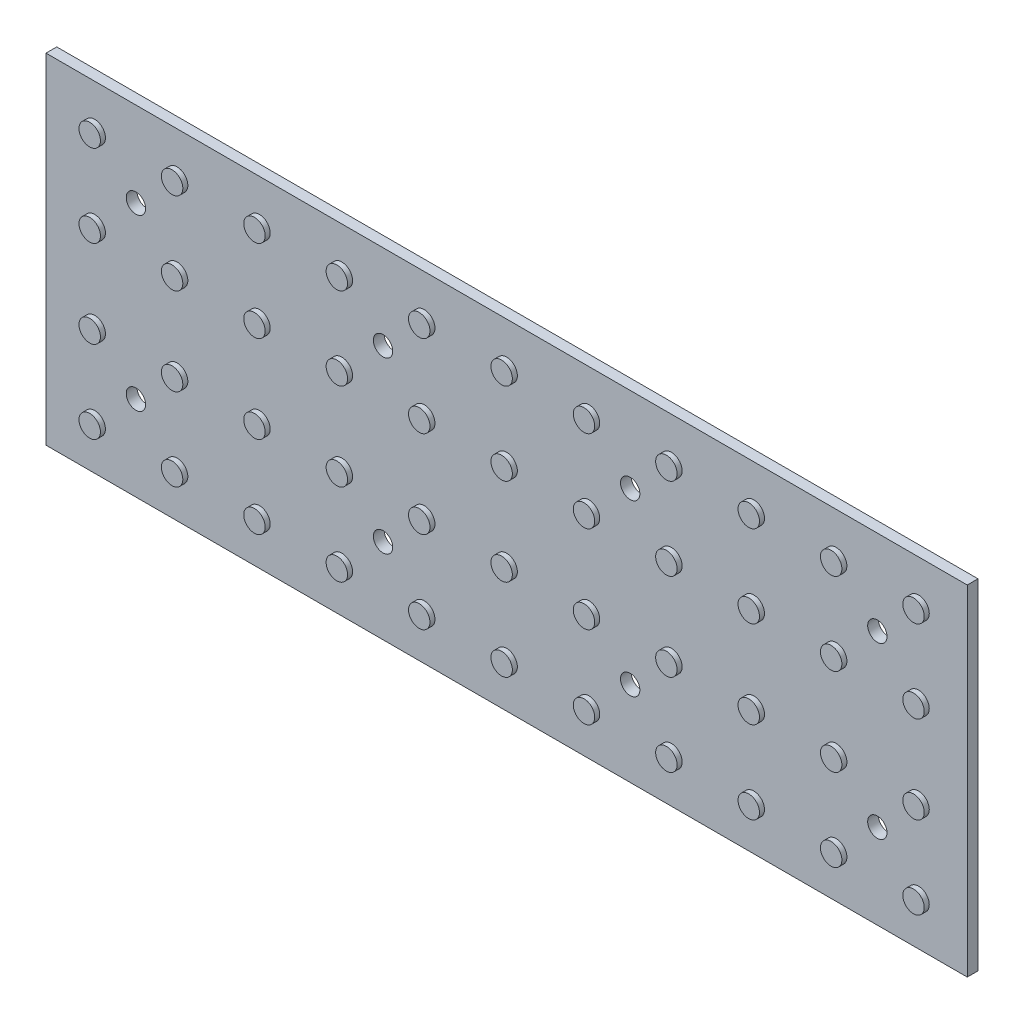
SolidWorks part; units mm, degrees
ref_plane "Front Plane" through (0, 0, 0) normal (0, 0, 1) x (1, 0, 0)
ref_plane "Top Plane" through (0, 0, 0) normal (0, 1, 0) x (1, 0, 0)
ref_plane "Right Plane" through (0, 0, 0) normal (1, 0, 0) x (0, 0, -1)
sketch "Sketch1" plane through (0, 0, 0) normal (0, 0, 1) x (1, 0, 0)
  line L1 (257.2, 0) -> (0, 0)
  line L2 (257.2, 0) -> (257.2, 94.8)
  line L3 (257.2, 94.8) -> (0, 94.8)
  line L4 (0, 0) -> (0, 94.8)
  dimension "D1" = 94.8
  dimension "D2" = 257.2
extrude "Boss-Extrude1" add sketch "Sketch1" along normal blind 3
ref_plane "Plane1" through (0, 47.4, 0) normal (0, -1, 0) x (-1, 0, 0)
ref_plane "Plane2" through (128.6, 0, 0) normal (-1, 0, 0) x (0, 0, 1)
sketch "Sketch2" plane through (0, 0, 3) normal (0, 0, 1) x (1, 0, 0)
  line L0 (0, 0) -> (257.2, 0) construction
  line L1 (0, 94.8) -> (0, 0) construction
  circle A0 centre (13.6, 12.2) radius 2.995
  dimension "D3" = 5.99
  dimension "D1" = 12.2
  dimension "D2" = 13.6
extrude "Boss-Extrude2" add sketch "Sketch2" along normal blind 1.4
pattern_linear "LPattern1" count 2 spacing 23 along (0, 1, 0) count 11 spacing 23 along (1, 0, 0) of "Boss-Extrude2"
mirror "Mirror4" about plane through (0, 47.4, 0) normal (0, -1, 0) of "LPattern1", "Boss-Extrude2"
sketch "Sketch3" plane through (0, 0, 3) normal (0, 0, 1) x (1, 0, 0)
  line L0 (-1.65, 47.4) -> (1.65, 47.4) construction
  line L1 (128.6, 1.65) -> (128.6, -1.65) construction
  circle A0 centre (25.1, 71.1) radius 2.7
  circle A1 centre (94.1, 71.1) radius 2.7
  circle A2 centre (163.1, 71.1) radius 2.7
  circle A3 centre (232.1, 71.1) radius 2.7
  dimension "D4" = 5.4
  dimension "D1" = 23.7
  dimension "D2" = 34.5
  dimension "D3" = 103.5
  dimension "D5" = 34.5
  dimension "D6" = 103.5
extrude "Cut-Extrude1" cut sketch "Sketch3" against normal through all
mirror "Mirror3" about plane through (0, 47.4, 0) normal (0, -1, 0) of "Cut-Extrude1"
